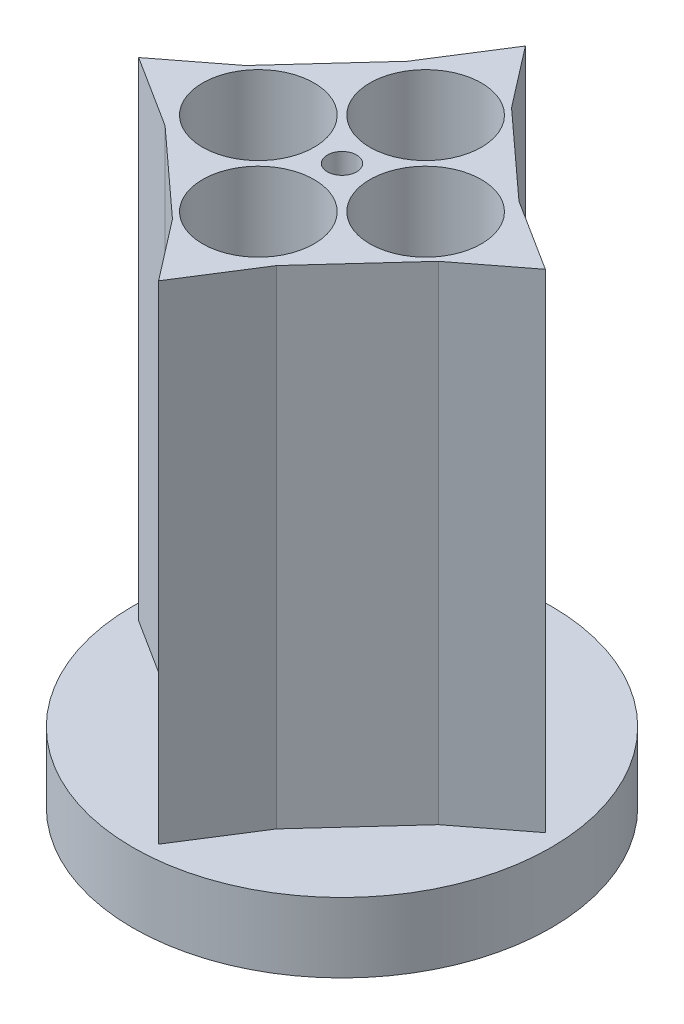
SolidWorks part; units mm, degrees
ref_plane "Front" through (0, 0, 0) normal (0, 0, 1) x (1, 0, 0)
ref_plane "Top" through (0, 0, 0) normal (0, 1, 0) x (1, 0, 0)
ref_plane "Right" through (0, 0, 0) normal (1, 0, 0) x (0, 0, -1)
sketch "Sketch1" plane through (0, 0, 0) normal (0, 1, 0) x (1, 0, 0)
  circle A0 centre (0, 0) radius 15
extrude "Boss-Extrude1" add sketch "Sketch1" along normal blind 40
sketch "Sketch2" plane through (0, 40, 0) normal (0, 1, 0) x (1, 0, 0)
  circle A0 centre (0, 6) radius 4
  circle A1 centre (6, 0) radius 4
  circle A2 centre (0, -6) radius 4
  circle A3 centre (-6, 0) radius 4
  point P11 (0, 0)
  dimension "D1" = 4
  dimension "D2" = 6
extrude "Cut-Extrude1" cut sketch "Sketch2" against normal blind 7
sketch "Sketch6" plane through (0, 33, 0) normal (0, 1, 0) x (1, 0, 0)
  line L0 (0, 0) -> (6, 0) construction
  line L1 (1.4, -5.5) -> (-1.4, -5.5)
  line L2 (5.5, 1.4) -> (6.5, 1.4)
  line L3 (5.5, 1.4) -> (5.5, -1.4)
  line L4 (5.5, -1.4) -> (6.5, -1.4)
  line L5 (6.5, 1.4) -> (6.5, -1.4)
  line L6 (5.5, 1.4) -> (6.5, -1.4) construction
  line L7 (5.5, -1.4) -> (6.5, 1.4) construction
  line L8 (1.4, -5.5) -> (1.4, -6.5)
  line L9 (1.4, -6.5) -> (-1.4, -6.5)
  line L10 (-1.4, -5.5) -> (-1.4, -6.5)
  line L11 (-5.5, -1.4) -> (-5.5, 1.4)
  line L12 (-5.5, -1.4) -> (-6.5, -1.4)
  line L13 (-6.5, -1.4) -> (-6.5, 1.4)
  line L14 (-5.5, 1.4) -> (-6.5, 1.4)
  line L15 (-1.4, 5.5) -> (1.4, 5.5)
  line L16 (-1.4, 5.5) -> (-1.4, 6.5)
  line L17 (-1.4, 6.5) -> (1.4, 6.5)
  line L18 (1.4, 5.5) -> (1.4, 6.5)
  point P23 (0, 0)
  dimension "D1" = 2.8
  dimension "D2" = 1
  dimension "D3" = 4
extrude "Cut-Extrude4" cut sketch "Sketch6" against normal blind 30
sketch "Sketch7" plane through (0, 0, 0) normal (0, -1, 0) x (1, 0, 0)
  circle A0 centre (0, 0) radius 9.5
extrude "Cut-Extrude5" cut sketch "Sketch7" against normal blind 3
sketch "Sketch8" plane through (0, 3, 0) normal (0, -1, 0) x (1, 0, 0)
  circle A0 centre (0, 0) radius 1.05
extrude "Cut-Extrude6" cut sketch "Sketch8" against normal up to next
sketch "Sketch9" plane through (0, 3, 0) normal (0, -1, 0) x (1, 0, 0)
  circle A0 centre (0, 0) radius 3.3991
extrude "Boss-Extrude2" add sketch "Sketch9" along normal blind 4
sketch "Sketch10" plane through (0, -1, 0) normal (0, -1, 0) x (1, 0, 0)
  circle A0 centre (0, 0) radius 2
extrude "Cut-Extrude7" cut sketch "Sketch10" against normal blind 4
sketch "Sketch13" plane through (0, 40, 0) normal (0, 1, 0) x (1, 0, 0)
  line L0 (13.8716, 0.7156) -> (8.693, 4)
  line L1 (8.693, 4) -> (2.6215, 9.5409)
  line L2 (2.6215, 9.5409) -> (-0.7156, 13.8716)
  line L3 (0.7156, -13.8716) -> (4, -8.693)
  line L4 (4, -8.693) -> (9.5409, -2.6215)
  line L5 (9.5409, -2.6215) -> (13.8716, 0.7156)
  line L6 (-13.8716, -0.7156) -> (-8.693, -4)
  line L7 (-8.693, -4) -> (-2.6215, -9.5409)
  line L8 (-2.6215, -9.5409) -> (0.7156, -13.8716)
  line L9 (-0.7156, 13.8716) -> (-4, 8.693)
  line L10 (-4, 8.693) -> (-9.5409, 2.6215)
  line L11 (-9.5409, 2.6215) -> (-13.8716, -0.7156)
  circle A2 centre (0, 6) radius 4
  circle A3 centre (0, 6) radius 4
  circle A4 centre (-6, 0) radius 4
  circle A5 centre (-6, 0) radius 4
  circle A6 centre (6, 0) radius 4
  circle A7 centre (6, 0) radius 4
  circle A8 centre (0, -6) radius 4
  circle A9 centre (0, -6) radius 4
  circle A10 centre (0, 0) radius 1.05
  circle A11 centre (0, 0) radius 1.05
  point P33 (0, 0)
  dimension "D1" = 170
  dimension "D2" = 170
  dimension "D4" = 0
  dimension "D5" = 0
  dimension "D6" = 0
  dimension "D7" = 0
  dimension "D8" = 0
  dimension "D3" = 4
extrude "Cut-Extrude9" cut sketch "Sketch13" against normal blind 35
